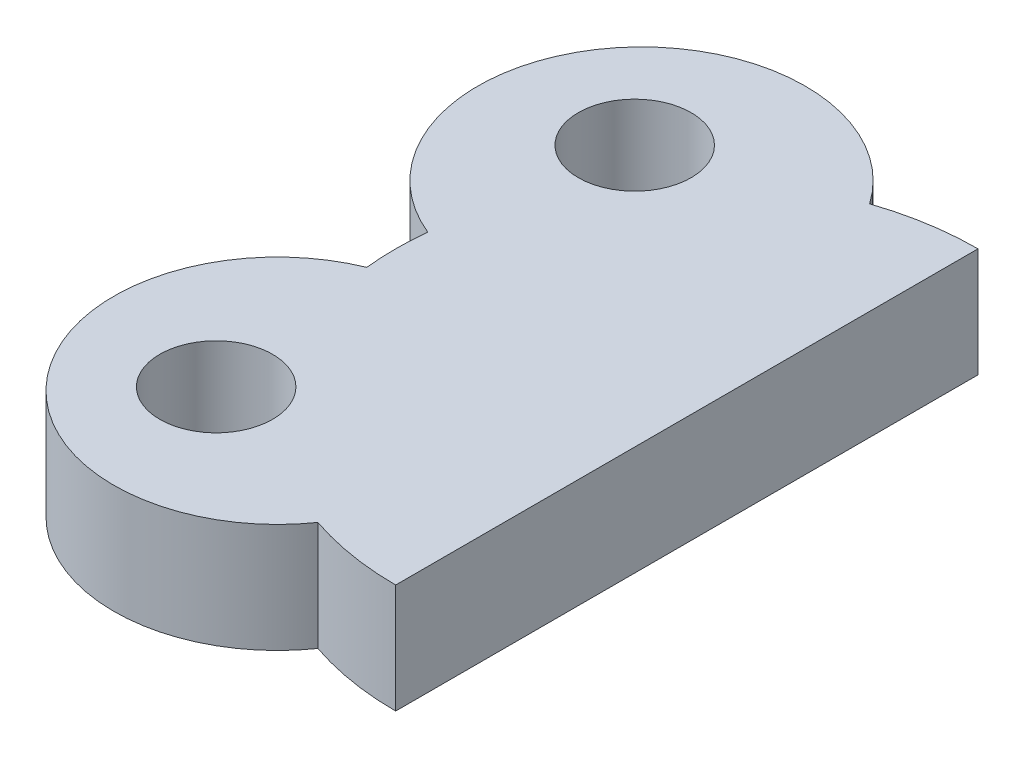
SolidWorks part; units mm, degrees
ref_plane "前视基准面" through (0, 0, 0) normal (0, 0, 1) x (1, 0, 0)
ref_plane "上视基准面" through (0, 0, 0) normal (0, 1, 0) x (1, 0, 0)
ref_plane "右视基准面" through (0, 0, 0) normal (1, 0, 0) x (0, 0, -1)
other "Configuration Table"
sketch "草图1" plane through (0, 0, 0) normal (0, 1, 0) x (1, 0, 0)
  line L0 (-10.5, 8) -> (-10.5, -8)
  arc A2 (-10.5, 8) -> (-13.058, 7.58) centre (-10.5, 0) ccw
  arc A3 (-13.058, 7.58) -> (-18.456, 0.838) centre (-16.745, 5) ccw
  arc A4 (-18.456, -0.838) -> (-13.058, -7.58) centre (-16.745, -5) ccw
  arc A5 (-18.456, 0.838) -> (-18.456, -0.838) centre (-10.5, 0) ccw
  arc A6 (-13.058, -7.58) -> (-10.5, -8) centre (-10.5, 0) ccw
  dimension "D4" = 16
  dimension "D7" = 9
  dimension "D8" = 9
  dimension "D5" = 5
  dimension "D6" = 5
extrude "凸台-拉伸1" add sketch "草图1" along normal blind 3
sketch "草图2" plane through (0, 3, 0) normal (0, 1, 0) x (1, 0, 0)
  line L0 (-10.5, 0) -> (-19.6957, 7.3624) construction
  line L1 (-10.5, -8) -> (-10.5, 8) construction
  line L2 (-10.5, 0) -> (-19.3258, -7.0663) construction
  circle A0 centre (-17.6817, 5.75) radius 1.55
  circle A1 centre (-17.6817, -5.75) radius 1.55
  dimension "D1" = 3.1
  dimension "D2" = 3.1
  dimension "D3" = 9.2
  dimension "D4" = 9.2
extrude "切除-拉伸1" cut sketch "草图2" against normal through all
